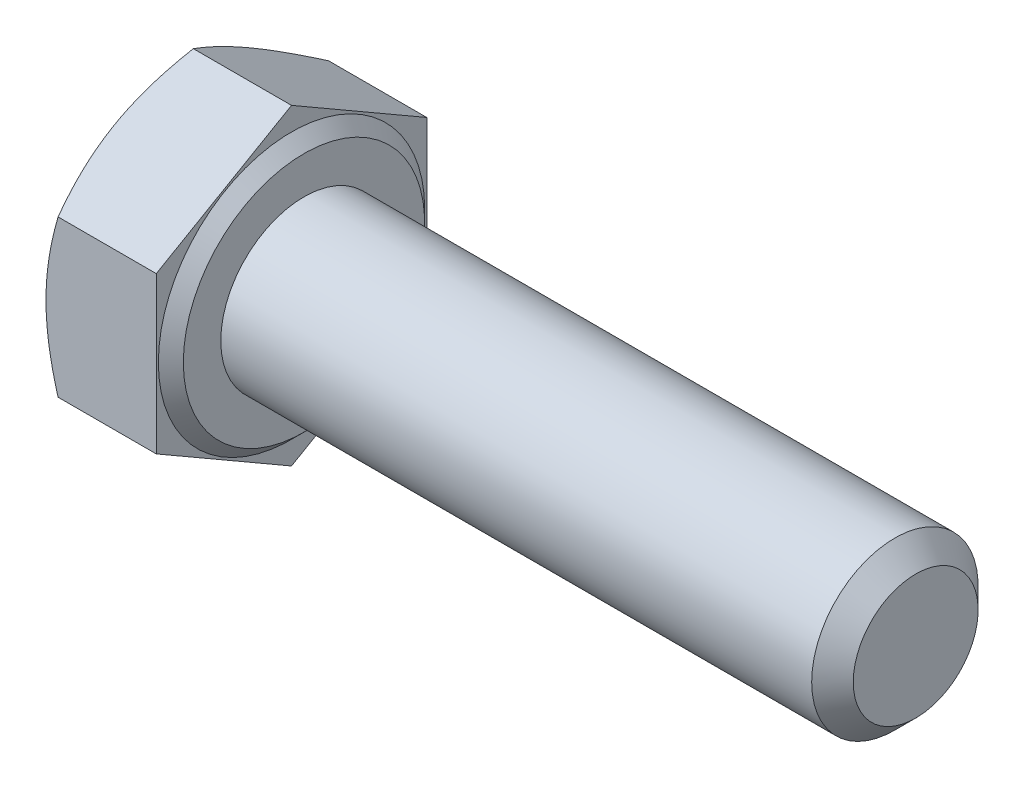
SolidWorks part; units mm, degrees
ref_plane "前视基准面" through (0, 0, 0) normal (0, 0, 1) x (1, 0, 0)
ref_plane "上视基准面" through (0, 0, 0) normal (0, 1, 0) x (1, 0, 0)
ref_plane "右视基准面" through (0, 0, 0) normal (1, 0, 0) x (0, 0, -1)
sketch "草图1" plane through (0, 0, 0) normal (1, 0, 0) x (0, 0, 1)
  line L1 (0, 7.5056) -> (-6.5, 3.7528)
  line L2 (-6.5, 3.7528) -> (-6.5, -3.7528)
  line L3 (-6.5, -3.7528) -> (0, -7.5056)
  line L4 (0, -7.5056) -> (6.5, -3.7528)
  line L5 (6.5, -3.7528) -> (6.5, 3.7528)
  line L6 (6.5, 3.7528) -> (0, 7.5056)
  circle A0 centre (0, 0) radius 6.5 construction
  dimension "s" = 13
extrude "拉伸1" add sketch "草图1" along normal mid plane 5.3
sketch "草图2" plane through (0, 0, 0) normal (0, 0, 1) x (1, 0, 0)
  line L0 (-3.243, 0) -> (14.063, 0) construction
  line L1 (-2.65, 6.5) -> (0.0347, 11.15)
  line L2 (-2.65, 7.5056) -> (-2.65, 3.7528) construction
  line L4 (-2.65, 6.5) -> (-2.65, 11.15)
  line L5 (-2.65, 11.15) -> (0.0347, 11.15)
  dimension "D1" = 30
  dimension "s" = 13
revolve "切除-旋转2" cut sketch "草图2" angle 360 about L0
sketch "草图3" plane through (0, 0, 0) normal (0, 0, 1) x (1, 0, 0)
  line L0 (-4.5438, 0) -> (36.9739, 0) construction
  line L1 (2.65, 0) -> (2.65, 6.4)
  line L2 (2.65, 3.7528) -> (2.65, -3.7528) construction
  line L4 (3.25, 5.8) -> (3.25, 4)
  line L5 (3.25, 4) -> (32.65, 4)
  line L6 (32.65, 4) -> (32.65, 0)
  line L7 (32.65, 0) -> (2.65, 0)
  line L8 (2.65, 7.5056) -> (2.65, 3.7528) construction
  line L9 (2.65, 6.4) -> (3.25, 5.8)
  dimension "D1" = 0.6
  dimension "l" = 30
  dimension "d" = 8
  dimension "c" = 0.6
  dimension "dw" = 11.6
revolve "旋转1" add sketch "草图3" angle 360 about L0
cosmetic thread "装饰螺纹线1" parameters "D1"=22, "D2"=6
chamfer "倒角2" distance 1 angle 45 1 edges at (32.65, 0, 4)
